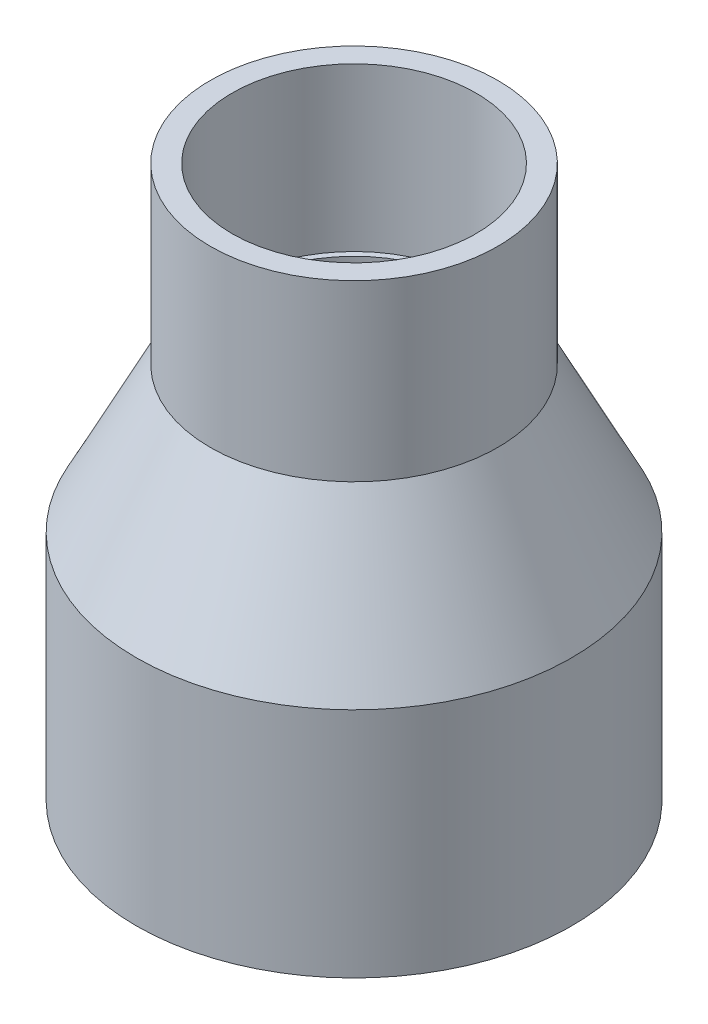
SolidWorks part; units mm, degrees
ref_plane "Front Plane" through (0, 0, 0) normal (0, 0, 1) x (1, 0, 0)
ref_plane "Top Plane" through (0, 0, 0) normal (0, 1, 0) x (1, 0, 0)
ref_plane "Right Plane" through (0, 0, 0) normal (1, 0, 0) x (0, 0, -1)
sketch "Sketch1" plane through (0, 0, 0) normal (0, 1, 0) x (1, 0, 0)
  circle A0 centre (0, 0) radius 37.5
  dimension "D1" = 75
extrude "Boss-Extrude1" add sketch "Sketch1" along normal blind 65
chamfer "Chamfer1" distance 25 angle 27 1 edges at (0, 65, 37.5)
sketch "Sketch3" plane through (0, 65, 0) normal (0, 1, 0) x (1, 0, 0)
  circle A0 centre (0, 0) radius 21
  dimension "D1" = 42
extrude "Cut-Extrude1" cut sketch "Sketch3" against normal blind 30
sketch "Sketch4" plane through (0, 0, 0) normal (0, -1, 0) x (1, 0, 0)
  circle A0 centre (0, 0) radius 35
  dimension "D1" = 70
extrude "Cut-Extrude2" cut sketch "Sketch4" against normal blind 39
sketch "Sketch5" plane through (0, 65, 0) normal (0, 1, 0) x (1, 0, 0)
  circle A0 centre (0, 0) radius 24.7619
  dimension "D1" = 49.5237
extrude "Boss-Extrude3" add sketch "Sketch5" along normal blind 30
sketch "Sketch6" plane through (0, 95, 0) normal (0, 1, 0) x (1, 0, 0)
  circle A0 centre (0, 0) radius 21
  dimension "D1" = 42
extrude "Cut-Extrude3" cut sketch "Sketch6" against normal blind 28
sketch "Sketch7" plane through (0, 67, 0) normal (0, 1, 0) x (1, 0, 0)
  circle A0 centre (0, 0) radius 20
  dimension "D1" = 40
extrude "Cut-Extrude4" cut sketch "Sketch7" against normal blind 30
